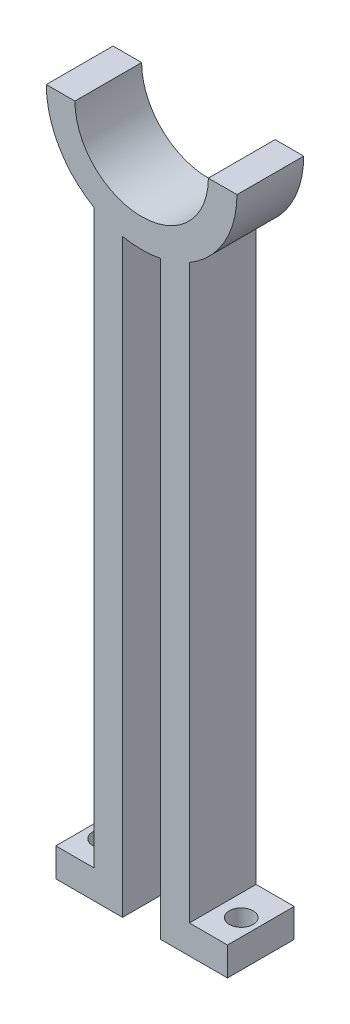
SolidWorks part; units mm, degrees
material "AISI 304"
ref_plane "Front Plane" through (0, 0, 0) normal (0, 0, 1) x (1, 0, 0)
ref_plane "Top Plane" through (0, 0, 0) normal (0, 1, 0) x (1, 0, 0)
ref_plane "Right Plane" through (0, 0, 0) normal (1, 0, 0) x (0, 0, -1)
sketch "Sketch2" plane through (0, 0, 0) normal (0, 0, 1) x (1, 0, 0)
  line L0 (0, 0) -> (0, -28.351) construction
  line L1 (-5.0049, -8.6574) -> (-5.0049, -68.6574)
  line L2 (-5.0049, -68.6574) -> (-9.0049, -68.6574)
  line L3 (-9.0049, -68.6574) -> (-9.0049, -71.6574)
  line L4 (-9.0049, -71.6574) -> (-2.0049, -71.6574)
  line L5 (-2.0049, -71.6574) -> (-2.0049, -9.797)
  line L6 (5.0049, -68.6574) -> (9.0049, -68.6574)
  line L7 (9.0049, -68.6574) -> (9.0049, -71.6574)
  line L8 (9.0049, -71.6574) -> (2.0049, -71.6574)
  line L9 (2.0049, -71.6574) -> (2.0049, -9.797)
  line L10 (5.0049, -8.6574) -> (5.0049, -68.6574)
  line L11 (-10, 0) -> (-7, 0)
  line L12 (7, 0) -> (10, 0)
  arc A0 (-7, 0) -> (7, 0) centre (0, 0) ccw
  arc A1 (-10, 0) -> (-5.0049, -8.6574) centre (0, 0) ccw
  arc A2 (-2.0049, -9.797) -> (2.0049, -9.797) centre (0, 0) ccw
  arc A3 (5.0049, -8.6574) -> (10, 0) centre (0, 0) ccw
  dimension "D1" = 14
  dimension "D2" = 20
  dimension "D3" = 7
  dimension "D4" = 3
  dimension "D5" = 3
  dimension "D6" = 60
extrude "Boss-Extrude1" add sketch "Sketch2" along normal blind 7
sketch "Sketch3" plane through (0, -68.6574, 0) normal (0, 1, 0) x (1, 0, 0)
  circle A0 centre (-7.0845, -3.7953) radius 1.25
  circle A1 centre (7.2394, -3.7953) radius 1.25
  dimension "D1" = 2.5
  dimension "D2" = 2.5
extrude "Cut-Extrude1" cut sketch "Sketch3" against normal blind 10
